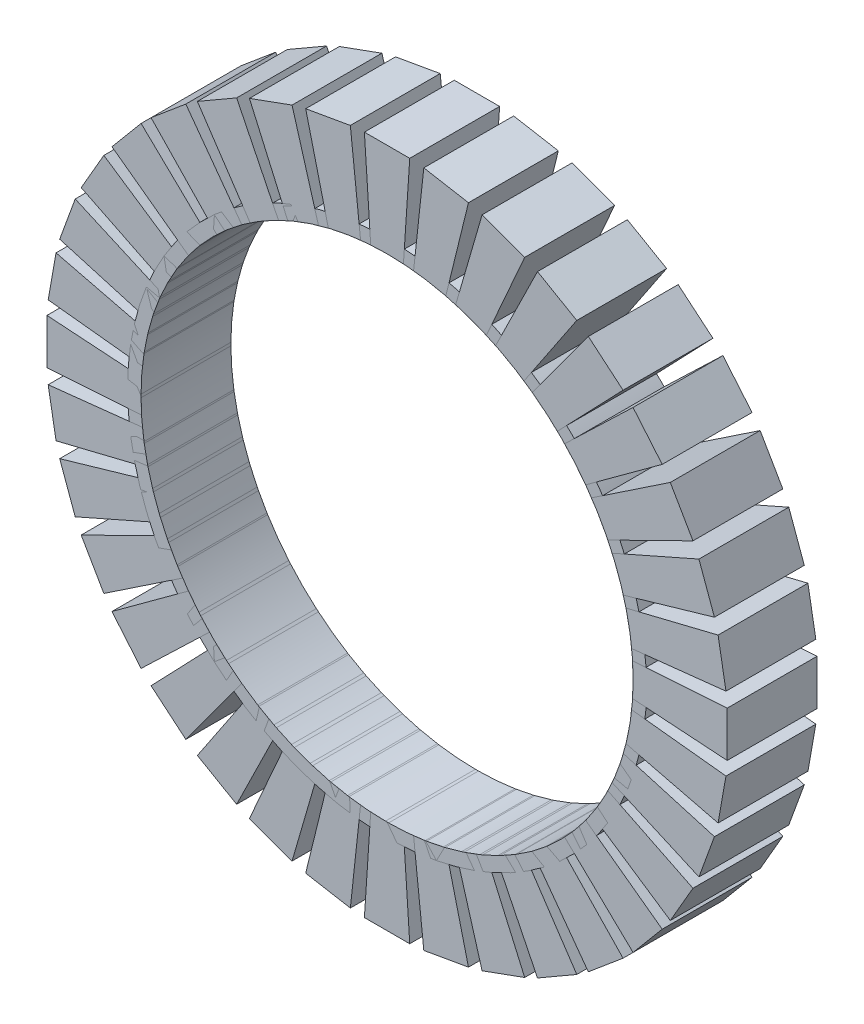
SolidWorks part; units mm, degrees
ref_plane "Front Plane" through (0, 0, 0) normal (0, 0, 1) x (1, 0, 0)
ref_plane "Top Plane" through (0, 0, 0) normal (0, 1, 0) x (1, 0, 0)
ref_plane "Right Plane" through (0, 0, 0) normal (1, 0, 0) x (0, 0, -1)
sketch "Sketch1" plane through (0, 0, 0) normal (0, 0, 1) x (1, 0, 0)
  line L0 (0, 0) -> (0, 40.5) construction
  line L1 (0, 0) -> (7.0328, 39.8847) construction
  line L2 (0, 0) -> (13.8518, 38.0576) construction
  line L3 (0, 0) -> (20.25, 35.074) construction
  line L4 (0, 0) -> (26.0329, 31.0248) construction
  line L5 (0, 0) -> (31.0248, 26.0329) construction
  line L6 (0, 0) -> (35.074, 20.25) construction
  line L7 (0, 0) -> (38.0576, 13.8518) construction
  line L8 (0, 0) -> (39.8847, 7.0328) construction
  line L9 (0, 0) -> (40.5, 0) construction
  line L10 (0, 0) -> (39.8847, -7.0328) construction
  line L11 (0, 0) -> (38.0576, -13.8518) construction
  line L12 (0, 0) -> (35.074, -20.25) construction
  line L13 (0, 0) -> (31.0248, -26.0329) construction
  line L14 (0, 0) -> (26.0329, -31.0248) construction
  line L15 (0, 0) -> (20.25, -35.074) construction
  line L16 (0, 0) -> (13.8518, -38.0576) construction
  line L17 (0, 0) -> (7.0328, -39.8847) construction
  line L18 (0, 0) -> (0, -40.5) construction
  line L19 (0, 0) -> (-7.0328, -39.8847) construction
  line L20 (0, 0) -> (-13.8518, -38.0576) construction
  line L21 (0, 0) -> (-20.25, -35.074) construction
  line L22 (0, 0) -> (-26.0329, -31.0248) construction
  line L23 (0, 0) -> (-31.0248, -26.0329) construction
  line L24 (0, 0) -> (-35.074, -20.25) construction
  line L25 (0, 0) -> (-38.0576, -13.8518) construction
  line L26 (0, 0) -> (-39.8847, -7.0328) construction
  line L27 (0, 0) -> (-40.5, 0) construction
  line L28 (0, 0) -> (-39.8847, 7.0328) construction
  line L29 (0, 0) -> (-38.0576, 13.8518) construction
  line L30 (0, 0) -> (-35.074, 20.25) construction
  line L31 (0, 0) -> (-31.0248, 26.0329) construction
  line L32 (0, 0) -> (-26.0329, 31.0248) construction
  line L33 (0, 0) -> (-20.25, 35.074) construction
  line L34 (0, 0) -> (-13.8518, 38.0576) construction
  line L35 (0, 0) -> (-7.0328, 39.8847) construction
  line L36 (-2.7, 40.5) -> (2.7, 40.5)
  line L37 (-1.949, 29.2351) -> (-2.7, 40.5)
  line L38 (1.949, 29.2351) -> (2.7, 40.5)
  line L39 (0, 0) -> (-1.949, 29.2351) construction
  line L40 (0, 0) -> (1.949, 29.2351) construction
  line L41 (3.1572, 29.1294) -> (4.3738, 40.3536)
  line L42 (6.996, 28.4525) -> (9.6917, 39.4159)
  line L43 (4.3738, 40.3536) -> (9.6917, 39.4159)
  line L44 (8.1675, 28.1386) -> (11.3146, 38.981)
  line L45 (11.8305, 26.8054) -> (16.389, 37.1341)
  line L46 (11.3146, 38.981) -> (16.389, 37.1341)
  line L47 (12.9297, 26.2928) -> (17.9117, 36.424)
  line L48 (16.3054, 24.3438) -> (22.5883, 33.724)
  line L49 (17.9117, 36.424) -> (22.5883, 33.724)
  line L50 (17.2989, 23.6482) -> (23.9646, 32.7603)
  line L51 (20.285, 21.1426) -> (28.1012, 29.2893)
  line L52 (23.9646, 32.7603) -> (28.1012, 29.2893)
  line L53 (21.1426, 20.285) -> (29.2893, 28.1012)
  line L54 (23.6482, 17.2989) -> (32.7603, 23.9646)
  line L55 (29.2893, 28.1012) -> (32.7603, 23.9646)
  line L56 (24.3438, 16.3054) -> (33.724, 22.5883)
  line L57 (26.2928, 12.9297) -> (36.424, 17.9117)
  line L58 (33.724, 22.5883) -> (36.424, 17.9117)
  line L59 (26.8054, 11.8305) -> (37.1341, 16.389)
  line L60 (28.1386, 8.1675) -> (38.981, 11.3146)
  line L61 (37.1341, 16.389) -> (38.981, 11.3146)
  line L62 (28.4525, 6.996) -> (39.4159, 9.6917)
  line L63 (29.1294, 3.1572) -> (40.3536, 4.3738)
  line L64 (39.4159, 9.6917) -> (40.3536, 4.3738)
  line L65 (29.2351, 1.949) -> (40.5, 2.7)
  line L66 (29.2351, -1.949) -> (40.5, -2.7)
  line L67 (40.5, 2.7) -> (40.5, -2.7)
  line L68 (29.1294, -3.1572) -> (40.3536, -4.3738)
  line L69 (28.4525, -6.996) -> (39.4159, -9.6917)
  line L70 (40.3536, -4.3738) -> (39.4159, -9.6917)
  line L71 (28.1386, -8.1675) -> (38.981, -11.3146)
  line L72 (26.8054, -11.8305) -> (37.1341, -16.389)
  line L73 (38.981, -11.3146) -> (37.1341, -16.389)
  line L74 (26.2928, -12.9297) -> (36.424, -17.9117)
  line L75 (24.3438, -16.3054) -> (33.724, -22.5883)
  line L76 (36.424, -17.9117) -> (33.724, -22.5883)
  line L77 (23.6482, -17.2989) -> (32.7603, -23.9646)
  line L78 (21.1426, -20.285) -> (29.2893, -28.1012)
  line L79 (32.7603, -23.9646) -> (29.2893, -28.1012)
  line L80 (20.285, -21.1426) -> (28.1012, -29.2893)
  line L81 (17.2989, -23.6482) -> (23.9646, -32.7603)
  line L82 (28.1012, -29.2893) -> (23.9646, -32.7603)
  line L83 (16.3054, -24.3438) -> (22.5883, -33.724)
  line L84 (12.9297, -26.2928) -> (17.9117, -36.424)
  line L85 (22.5883, -33.724) -> (17.9117, -36.424)
  line L86 (11.8305, -26.8054) -> (16.389, -37.1341)
  line L87 (8.1675, -28.1386) -> (11.3146, -38.981)
  line L88 (16.389, -37.1341) -> (11.3146, -38.981)
  line L89 (6.996, -28.4525) -> (9.6917, -39.4159)
  line L90 (3.1572, -29.1294) -> (4.3738, -40.3536)
  line L91 (9.6917, -39.4159) -> (4.3738, -40.3536)
  line L92 (1.949, -29.2351) -> (2.7, -40.5)
  line L93 (-1.949, -29.2351) -> (-2.7, -40.5)
  line L94 (2.7, -40.5) -> (-2.7, -40.5)
  line L95 (-3.1572, -29.1294) -> (-4.3738, -40.3536)
  line L96 (-6.996, -28.4525) -> (-9.6917, -39.4159)
  line L97 (-4.3738, -40.3536) -> (-9.6917, -39.4159)
  line L98 (-8.1675, -28.1386) -> (-11.3146, -38.981)
  line L99 (-11.8305, -26.8054) -> (-16.389, -37.1341)
  line L100 (-11.3146, -38.981) -> (-16.389, -37.1341)
  line L101 (-12.9297, -26.2928) -> (-17.9117, -36.424)
  line L102 (-16.3054, -24.3438) -> (-22.5883, -33.724)
  line L103 (-17.9117, -36.424) -> (-22.5883, -33.724)
  line L104 (-17.2989, -23.6482) -> (-23.9646, -32.7603)
  line L105 (-20.285, -21.1426) -> (-28.1012, -29.2893)
  line L106 (-23.9646, -32.7603) -> (-28.1012, -29.2893)
  line L107 (-21.1426, -20.285) -> (-29.2893, -28.1012)
  line L108 (-23.6482, -17.2989) -> (-32.7603, -23.9646)
  line L109 (-29.2893, -28.1012) -> (-32.7603, -23.9646)
  line L110 (-24.3438, -16.3054) -> (-33.724, -22.5883)
  line L111 (-26.2928, -12.9297) -> (-36.424, -17.9117)
  line L112 (-33.724, -22.5883) -> (-36.424, -17.9117)
  line L113 (-26.8054, -11.8305) -> (-37.1341, -16.389)
  line L114 (-28.1386, -8.1675) -> (-38.981, -11.3146)
  line L115 (-37.1341, -16.389) -> (-38.981, -11.3146)
  line L116 (-28.4525, -6.996) -> (-39.4159, -9.6917)
  line L117 (-29.1294, -3.1572) -> (-40.3536, -4.3738)
  line L118 (-39.4159, -9.6917) -> (-40.3536, -4.3738)
  line L119 (-29.2351, -1.949) -> (-40.5, -2.7)
  line L120 (-29.2351, 1.949) -> (-40.5, 2.7)
  line L121 (-40.5, -2.7) -> (-40.5, 2.7)
  line L122 (-29.1294, 3.1572) -> (-40.3536, 4.3738)
  line L123 (-28.4525, 6.996) -> (-39.4159, 9.6917)
  line L124 (-40.3536, 4.3738) -> (-39.4159, 9.6917)
  line L125 (-28.1386, 8.1675) -> (-38.981, 11.3146)
  line L126 (-26.8054, 11.8305) -> (-37.1341, 16.389)
  line L127 (-38.981, 11.3146) -> (-37.1341, 16.389)
  line L128 (-26.2928, 12.9297) -> (-36.424, 17.9117)
  line L129 (-24.3438, 16.3054) -> (-33.724, 22.5883)
  line L130 (-36.424, 17.9117) -> (-33.724, 22.5883)
  line L131 (-23.6482, 17.2989) -> (-32.7603, 23.9646)
  line L132 (-21.1426, 20.285) -> (-29.2893, 28.1012)
  line L133 (-32.7603, 23.9646) -> (-29.2893, 28.1012)
  line L134 (-20.285, 21.1426) -> (-28.1012, 29.2893)
  line L135 (-17.2989, 23.6482) -> (-23.9646, 32.7603)
  line L136 (-28.1012, 29.2893) -> (-23.9646, 32.7603)
  line L137 (-16.3054, 24.3438) -> (-22.5883, 33.724)
  line L138 (-12.9297, 26.2928) -> (-17.9117, 36.424)
  line L139 (-22.5883, 33.724) -> (-17.9117, 36.424)
  line L140 (-11.8305, 26.8054) -> (-16.389, 37.1341)
  line L141 (-8.1675, 28.1386) -> (-11.3146, 38.981)
  line L142 (-16.389, 37.1341) -> (-11.3146, 38.981)
  line L143 (-6.996, 28.4525) -> (-9.6917, 39.4159)
  line L144 (-3.1572, 29.1294) -> (-4.3738, 40.3536)
  line L145 (-9.6917, 39.4159) -> (-4.3738, 40.3536)
  arc A0 (-18.8337, 22.4451) -> (14.65, 25.3745) centre (0, 0) ccw construction
  circle A1 centre (0, 0) radius 40.5 construction
  arc A2 (-1.949, 29.2351) -> (-5.0879, 28.8549) centre (0, 0) ccw construction
  arc A3 (-5.0879, 28.8549) -> (-10.0212, 27.533) centre (0, 0) ccw construction
  arc A4 (-10.0212, 27.533) -> (-14.65, 25.3745) centre (0, 0) ccw construction
  arc A5 (-14.65, 25.3745) -> (-18.8337, 22.4451) centre (0, 0) ccw construction
  arc A6 (14.65, 25.3745) -> (10.0212, 27.533) centre (0, 0) ccw construction
  arc A7 (1.949, 29.2351) -> (-1.949, 29.2351) centre (0, 0) ccw
  arc A8 (10.0212, 27.533) -> (5.0879, 28.8549) centre (0, 0) ccw construction
  arc A9 (5.0879, 28.8549) -> (1.949, 29.2351) centre (0, 0) ccw construction
  arc A10 (6.996, 28.4525) -> (3.1572, 29.1294) centre (0, 0) ccw
  arc A11 (11.8305, 26.8054) -> (8.1675, 28.1386) centre (0, 0) ccw
  arc A12 (16.3054, 24.3438) -> (12.9297, 26.2928) centre (0, 0) ccw
  arc A13 (20.285, 21.1426) -> (17.2989, 23.6482) centre (0, 0) ccw
  arc A14 (23.6482, 17.2989) -> (21.1426, 20.285) centre (0, 0) ccw
  arc A15 (26.2928, 12.9297) -> (24.3438, 16.3054) centre (0, 0) ccw
  arc A16 (28.1386, 8.1675) -> (26.8054, 11.8305) centre (0, 0) ccw
  arc A17 (29.1294, 3.1572) -> (28.4525, 6.996) centre (0, 0) ccw
  arc A18 (29.2351, -1.949) -> (29.2351, 1.949) centre (0, 0) ccw
  arc A19 (28.4525, -6.996) -> (29.1294, -3.1572) centre (0, 0) ccw
  arc A20 (26.8054, -11.8305) -> (28.1386, -8.1675) centre (0, 0) ccw
  arc A21 (24.3438, -16.3054) -> (26.2928, -12.9297) centre (0, 0) ccw
  arc A22 (21.1426, -20.285) -> (23.6482, -17.2989) centre (0, 0) ccw
  arc A23 (17.2989, -23.6482) -> (20.285, -21.1426) centre (0, 0) ccw
  arc A24 (12.9297, -26.2928) -> (16.3054, -24.3438) centre (0, 0) ccw
  arc A25 (8.1675, -28.1386) -> (11.8305, -26.8054) centre (0, 0) ccw
  arc A26 (3.1572, -29.1294) -> (6.996, -28.4525) centre (0, 0) ccw
  arc A27 (-1.949, -29.2351) -> (1.949, -29.2351) centre (0, 0) ccw
  arc A28 (-6.996, -28.4525) -> (-3.1572, -29.1294) centre (0, 0) ccw
  arc A29 (-11.8305, -26.8054) -> (-8.1675, -28.1386) centre (0, 0) ccw
  arc A30 (-16.3054, -24.3438) -> (-12.9297, -26.2928) centre (0, 0) ccw
  arc A31 (-20.285, -21.1426) -> (-17.2989, -23.6482) centre (0, 0) ccw
  arc A32 (-23.6482, -17.2989) -> (-21.1426, -20.285) centre (0, 0) ccw
  arc A33 (-26.2928, -12.9297) -> (-24.3438, -16.3054) centre (0, 0) ccw
  arc A34 (-28.1386, -8.1675) -> (-26.8054, -11.8305) centre (0, 0) ccw
  arc A35 (-29.1294, -3.1572) -> (-28.4525, -6.996) centre (0, 0) ccw
  arc A36 (-29.2351, 1.949) -> (-29.2351, -1.949) centre (0, 0) ccw
  arc A37 (-28.4525, 6.996) -> (-29.1294, 3.1572) centre (0, 0) ccw
  arc A38 (-26.8054, 11.8305) -> (-28.1386, 8.1675) centre (0, 0) ccw
  arc A39 (-24.3438, 16.3054) -> (-26.2928, 12.9297) centre (0, 0) ccw
  arc A40 (-21.1426, 20.285) -> (-23.6482, 17.2989) centre (0, 0) ccw
  arc A41 (-17.2989, 23.6482) -> (-20.285, 21.1426) centre (0, 0) ccw
  arc A42 (-12.9297, 26.2928) -> (-16.3054, 24.3438) centre (0, 0) ccw
  arc A43 (-8.1675, 28.1386) -> (-11.8305, 26.8054) centre (0, 0) ccw
  arc A44 (-3.1572, 29.1294) -> (-6.996, 28.4525) centre (0, 0) ccw
  circle A45 centre (0, 0) radius 29.3 construction
  circle A46 centre (0, 0) radius 30.9 construction
  point P42 (0, 0)
  point P43 (0, 40.5)
  point P194 (0, 0)
  point P195 (0, 0)
  dimension "D1" = 58.6
  dimension "D2" = 81
  dimension "D6" = 61.8
  dimension "D3" = 36
  dimension "D4" = 5.4
  dimension "D5" = 36
extrude "Boss-Extrude1" add sketch "Sketch1" along normal blind 10.7
sketch "Sketch2" plane through (0, 0, 0) normal (0, 0, 1) x (1, 0, 0)
  circle A0 centre (0, 0) radius 29.3
  circle A1 centre (0, 0) radius 30.9
  dimension "D1" = 58.6
  dimension "D2" = 61.8
extrude "Boss-Extrude2" add sketch "Sketch2" along normal blind 10.7 separate body
